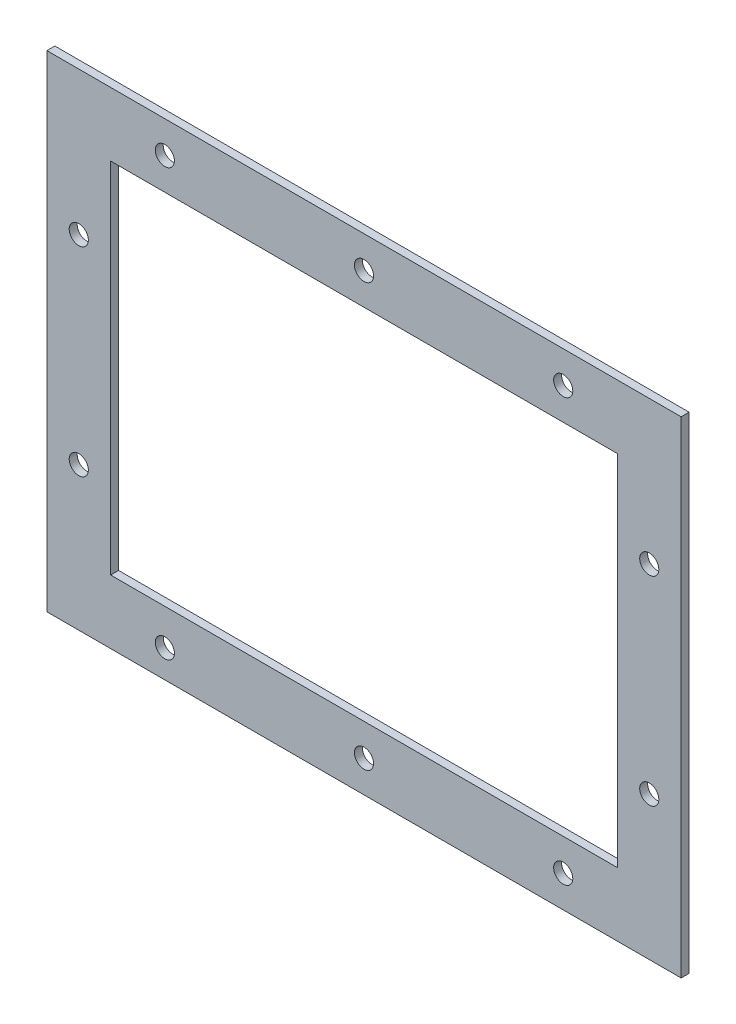
SolidWorks part; units mm, degrees
material "ASTM A36 Steel"
ref_plane "Front Plane" through (0, 0, 0) normal (0, 0, 1) x (1, 0, 0)
ref_plane "Top Plane" through (0, 0, 0) normal (0, 1, 0) x (1, 0, 0)
ref_plane "Right Plane" through (0, 0, 0) normal (1, 0, 0) x (0, 0, -1)
sketch "Sketch1" plane through (0, 0, 0) normal (0, 0, 1) x (1, 0, 0)
  line L0 (164.2801, -150.5) -> (164.2801, 154.5)
  line L1 (-193.7199, -110.5) -> (124.2801, -110.5)
  line L2 (-193.7199, -110.5) -> (-193.7199, 114.5)
  line L3 (-193.7199, 114.5) -> (124.2801, 114.5)
  line L4 (124.2801, -110.5) -> (124.2801, 114.5)
  line L5 (-193.7199, -110.5) -> (124.2801, 114.5) construction
  line L6 (-193.7199, 114.5) -> (124.2801, -110.5) construction
  line L7 (-233.7199, 154.5) -> (164.2801, 154.5)
  line L8 (-233.7199, -150.5) -> (-233.7199, 154.5)
  line L9 (-233.7199, -150.5) -> (164.2801, -150.5)
  point P0 (-34.7199, 2)
  dimension "D1" = 225
  dimension "D2" = 318
  dimension "D3" = 40
extrude "Boss-Extrude1" add sketch "Sketch1" along normal blind 5
sketch "Sketch2" plane through (0, 0, 5) normal (0, 0, 1) x (1, 0, 0)
  line L0 (-233.7199, 154.5) -> (-233.7199, -150.5) construction
  line L1 (-233.7199, -150.5) -> (164.2801, -150.5) construction
  line L2 (164.2801, 154.5) -> (-233.7199, 154.5) construction
  line L3 (164.2801, -150.5) -> (164.2801, 154.5) construction
  line L4 (-233.7199, -150.5) -> (164.2801, -150.5) construction
  circle A0 centre (-213.7199, 64.5) radius 6
  circle A1 centre (-213.7199, -60.5) radius 6
  circle A5 centre (-159.6943, -133.0288) radius 6
  circle A6 centre (-34.7199, -130.5) radius 6
  circle A7 centre (90.2801, -130.5) radius 6
  circle A12 centre (90.2801, 134.5) radius 6
  circle A13 centre (-34.7199, 134.5) radius 6
  circle A14 centre (-159.7199, 134.5) radius 6
  circle A15 centre (144.2801, -60.5) radius 6
  circle A16 centre (144.2801, 64.5) radius 6
  dimension "D1" = 125
  dimension "D2" = 12
  dimension "D3" = 12
  dimension "D4" = 20
  dimension "D5" = 90
  dimension "D6" = 0
  dimension "D7" = 90
  dimension "D8" = 20
  dimension "D9" = 125
  dimension "D10" = 20
  dimension "D11" = 20
  dimension "D12" = 74
  dimension "D14" = 125
  dimension "D15" = 125
  dimension "D16" = 125
  dimension "D17" = 125
  dimension "D13" = 74
extrude "Cut-Extrude1" cut sketch "Sketch2" against normal blind 5
